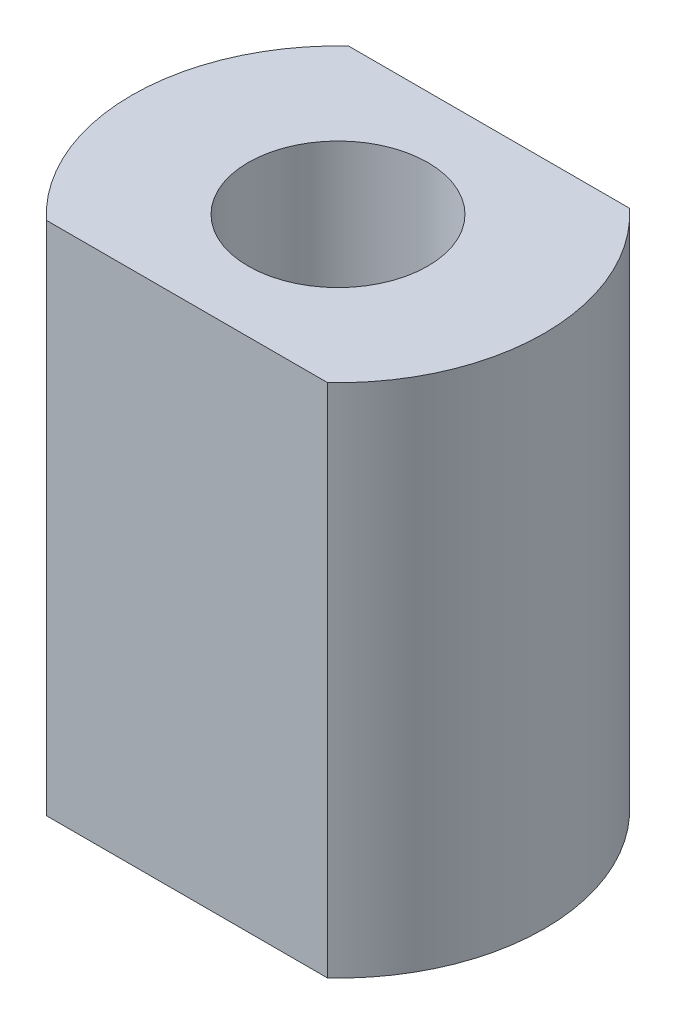
SolidWorks part; units mm, degrees
ref_plane "Front Plane" through (0, 0, 0) normal (0, 0, 1) x (1, 0, 0)
ref_plane "Top Plane" through (0, 0, 0) normal (0, 1, 0) x (1, 0, 0)
ref_plane "Right Plane" through (0, 0, 0) normal (1, 0, 0) x (0, 0, -1)
sketch "Sketch1" plane through (0, 0, 0) normal (0, 1, 0) x (1, 0, 0)
  line L0 (-1.9072, 2.05) -> (1.9072, 2.05)
  line L1 (-1.9072, -2.05) -> (1.9072, -2.05)
  arc A0 (-1.9072, 2.05) -> (-1.9072, -2.05) centre (0, 0) ccw
  arc A1 (1.9072, -2.05) -> (1.9072, 2.05) centre (0, 0) ccw
  dimension "D1" = 5.6
  dimension "D2" = 2.05
  dimension "D3" = 2.05
extrude "Boss-Extrude1" add sketch "Sketch1" along normal blind 7 contours A0 L1 A1 L0
hole_wizard "#2 Clearance Hole1" positions "Sketch2" profile "Sketch3" hole size "#2" standard "ANSI Inch" end condition through all
sketch "Sketch2" plane through (0, 7, 0) normal (0, 1, 0) x (1, 0, 0)
  point P0 (0, 0)
sketch "Sketch3" plane through (0, 7, 0) normal (1, 0, 0) x (0, 0, 1)
  line L0 (0, 0) -> (0, 7)
  line L1 (0, 7) -> (1.2192, 7)
  line L2 (1.2192, 7) -> (1.2192, 0)
  line L5 (1.2192, 0) -> (0, 0)
  line L11 (0, -6.35) -> (0, 107.95) construction
  dimension "Thru Hole Dia." = 2.4384
  dimension "Thru Hole Depth" = 7
